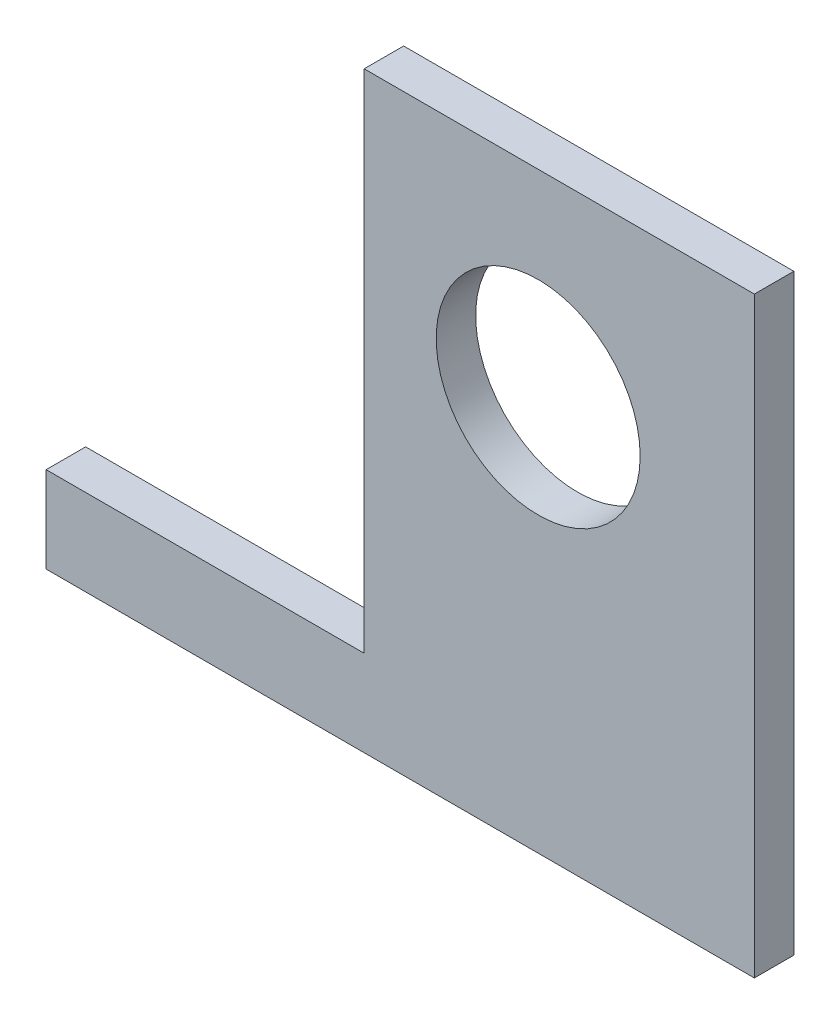
SolidWorks part; units mm, degrees
ref_plane "Front Plane" through (0, 0, 0) normal (0, 0, 1) x (1, 0, 0)
ref_plane "Top Plane" through (0, 0, 0) normal (0, 1, 0) x (1, 0, 0)
ref_plane "Right Plane" through (0, 0, 0) normal (1, 0, 0) x (0, 0, -1)
sketch "Sketch1" plane through (0, 0, 0) normal (0, 0, 1) x (1, 0, 0)
  line L1 (250, -75) -> (-250, -75)
  line L2 (250, -75) -> (250, 75)
  line L3 (250, 75) -> (-250, 75)
  line L4 (-250, -75) -> (-250, 75)
  line L5 (250, -75) -> (-250, 75) construction
  line L6 (250, 75) -> (-250, -75) construction
  point P0 (0, 0)
  dimension "D1" = 150
  dimension "D2" = 500
extrude "Boss-Extrude1" add sketch "Sketch1" along normal blind 10
sketch "Sketch2" plane through (0, 0, 10) normal (0, 0, 1) x (1, 0, 0)
  line L0 (-250, -75) -> (250, -75) construction
  circle A0 centre (195.2566, 25) radius 25.8316
  dimension "D1" = 100
extrude "Cut-Extrude1" cut sketch "Sketch2" against normal blind 10
sketch "Sketch3" plane through (0, 0, 10) normal (0, 0, 1) x (1, 0, 0)
  line L1 (-250, 75) -> (151.1909, 75)
  line L2 (-250, 75) -> (-250, -53.1827)
  line L3 (-250, -53.1827) -> (151.1909, -53.1827)
  line L4 (151.1909, 75) -> (151.1909, -53.1827)
extrude "Cut-Extrude2" cut sketch "Sketch3" against normal blind 10
sketch "Sketch5" plane through (0, 0, 10) normal (0, 0, 1) x (1, 0, 0)
  line L0 (-250, -75) -> (250, -75) construction
  line L1 (-570.6571, -31.3655) -> (70.6571, -31.3655)
  line L2 (-570.6571, -31.3655) -> (-570.6571, -75)
  line L3 (-570.6571, -75) -> (70.6571, -75)
  line L4 (70.6571, -31.3655) -> (70.6571, -75)
  line L5 (-570.6571, -31.3655) -> (70.6571, -75) construction
  line L6 (-570.6571, -75) -> (70.6571, -31.3655) construction
  point P0 (-250, -53.1827)
extrude "Cut-Extrude3" cut sketch "Sketch5" against normal blind 10
